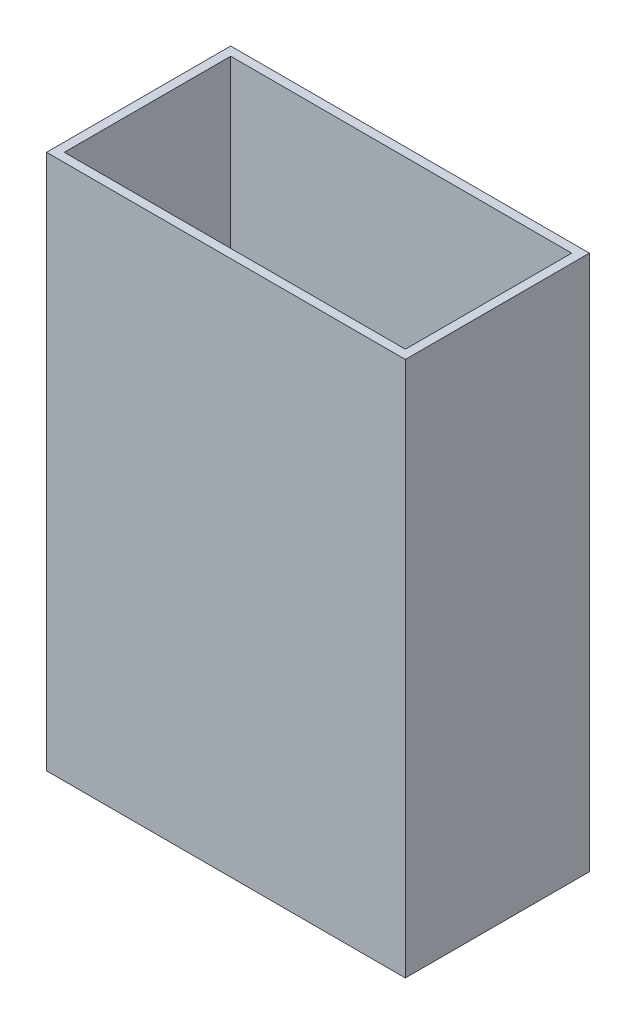
SolidWorks part; units mm, degrees
ref_plane "Спереди" through (0, 0, 0) normal (0, 0, 1) x (1, 0, 0)
ref_plane "Сверху" through (0, 0, 0) normal (0, 1, 0) x (1, 0, 0)
ref_plane "Справа" through (0, 0, 0) normal (1, 0, 0) x (0, 0, -1)
sketch "Эскиз1" plane through (0, 0, 0) normal (0, 1, 0) x (1, 0, 0)
  line L1 (-32.35, 16.6) -> (32.35, 16.6)
  line L2 (-32.35, 16.6) -> (-32.35, -16.6)
  line L3 (-32.35, -16.6) -> (32.35, -16.6)
  line L4 (32.35, 16.6) -> (32.35, -16.6)
  line L5 (-32.35, 16.6) -> (32.35, -16.6) construction
  line L6 (-32.35, -16.6) -> (32.35, 16.6) construction
  point P0 (0, 0)
  dimension "D1" = 64.7
  dimension "D2" = 33.2
extrude "Бобышка-Вытянуть1" add sketch "Эскиз1" along normal blind 1.6
sketch "Эскиз2" plane through (0, 1.6, 0) normal (0, 1, 0) x (1, 0, 0)
  line L1 (-32.35, 16.6) -> (32.35, 16.6)
  line L2 (-32.35, 16.6) -> (-32.35, -16.6)
  line L3 (-32.35, -16.6) -> (32.35, -16.6)
  line L4 (32.35, 16.6) -> (32.35, -16.6)
  line L5 (-30.75, 15) -> (30.75, 15)
  line L6 (-30.75, 15) -> (-30.75, -15)
  line L7 (-30.75, -15) -> (30.75, -15)
  line L8 (30.75, 15) -> (30.75, -15)
  line L9 (-30.75, 15) -> (30.75, -15) construction
  line L10 (-30.75, -15) -> (30.75, 15) construction
  point P6 (0, 0)
  dimension "D1" = 61.5
  dimension "D2" = 30
extrude "Бобышка-Вытянуть2" add sketch "Эскиз2" along normal blind 95
ref_plane "Плоскость1" through (-30.75, 1.6, -15) normal (0, 0, 1) x (1, 0, 0)
sketch "Эскиз4" plane through (0, 1.6, 0) normal (0, 1, 0) x (1, 0, 0)
  line L0 (0, 0) -> (0, 22.0777) construction
  line L1 (-30.75, 15) -> (-30.75, -15) construction
  line L2 (-30.75, 3) -> (-29.15, 3)
  line L3 (-30.75, 3) -> (-30.75, 1.4)
  line L4 (-30.75, 1.4) -> (-29.15, 1.4)
  line L5 (-29.15, 3) -> (-29.15, 1.4)
  line L6 (30.75, 15) -> (-30.75, 15) construction
  line L7 (30.75, -2.2) -> (29.15, -2.2)
  line L8 (-30.75, -0.6) -> (-29.15, -0.6)
  line L9 (-30.75, -0.6) -> (-30.75, -2.2)
  line L10 (-30.75, -2.2) -> (-29.15, -2.2)
  line L11 (-29.15, -0.6) -> (-29.15, -2.2)
  line L12 (29.15, -0.6) -> (29.15, -2.2)
  line L13 (30.75, -0.6) -> (30.75, -2.2)
  line L14 (30.75, -0.6) -> (29.15, -0.6)
  line L15 (30.75, 1.4) -> (29.15, 1.4)
  line L16 (30.75, 3) -> (30.75, 1.4)
  line L17 (29.15, 3) -> (29.15, 1.4)
  line L18 (30.75, 3) -> (29.15, 3)
  dimension "D1" = 12
  dimension "D2" = 1.6
  dimension "D3" = 1.6
  dimension "D4" = 2
  dimension "D5" = 1.6
  dimension "D6" = 1.6
extrude "Бобышка-Вытянуть3" add sketch "Эскиз4" along normal blind 60
